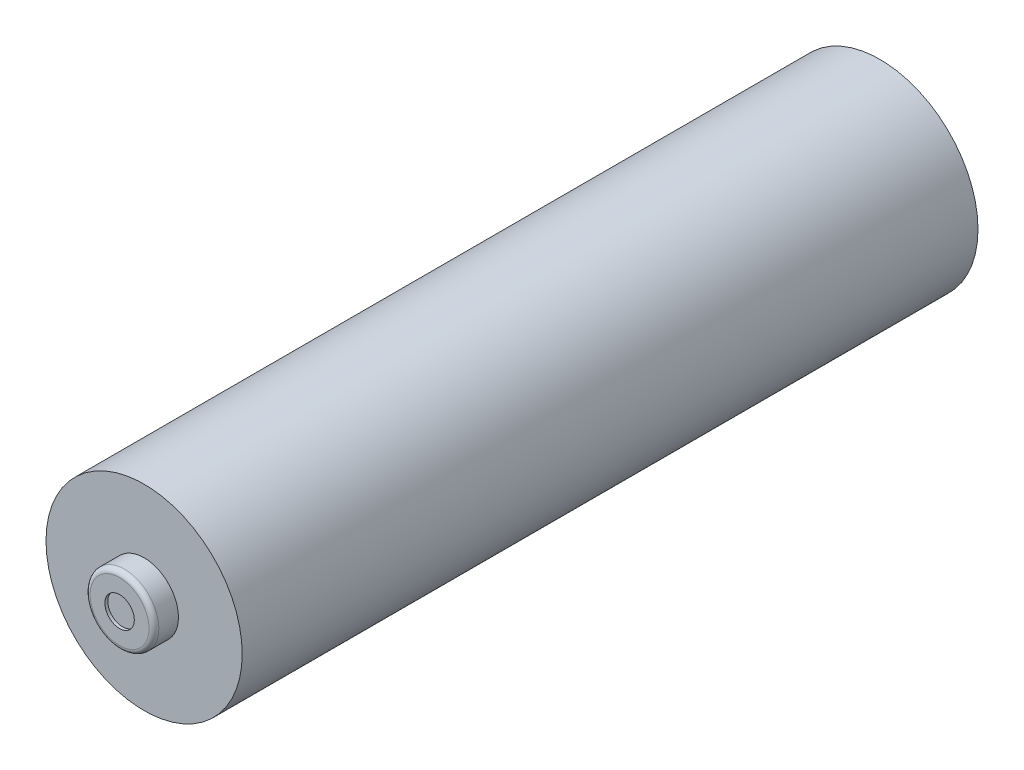
SolidWorks part; units mm, degrees
ref_plane "Front Plane" through (0, 0, 0) normal (0, 0, 1) x (1, 0, 0)
ref_plane "Top Plane" through (0, 0, 0) normal (0, 1, 0) x (1, 0, 0)
ref_plane "Right Plane" through (0, 0, 0) normal (1, 0, 0) x (0, 0, -1)
sketch "Sketch2" plane through (0, 0, 0) normal (0, 0, 1) x (1, 0, 0)
  circle A0 centre (0, 0) radius 254
  dimension "D1" = 508
extrude "Boss-Extrude2" add sketch "Sketch2" along normal blind 1905
sketch "Sketch3" plane through (0, 0, 1905) normal (0, 0, 1) x (1, 0, 0)
  circle A0 centre (0, 0) radius 88.9
  dimension "D1" = 177.8
extrude "Boss-Extrude3" add sketch "Sketch3" along normal blind 63.5 and the other way offset from surface (1968.5 mm away) 63.5 other way up to face at (254, 0, 0)
fillet "Fillet1" radius 12.7 2 edges at (88.9, 0, -63.5) (88.9, 0, 1968.5)
sketch "Sketch4" plane through (0, 0, -63.5) normal (0, 0, -1) x (-1, 0, 0)
  circle A0 centre (0, 0) radius 38.1
  dimension "D1" = 76.2
extrude "Cut-Extrude1" cut sketch "Sketch4" against normal blind 7.62
sketch "Sketch5" plane through (0, 0, 1968.5) normal (0, 0, 1) x (1, 0, 0)
  circle A0 centre (0, 0) radius 38.1
  dimension "D1" = 76.2
extrude "Cut-Extrude2" cut sketch "Sketch5" against normal blind 7.62
